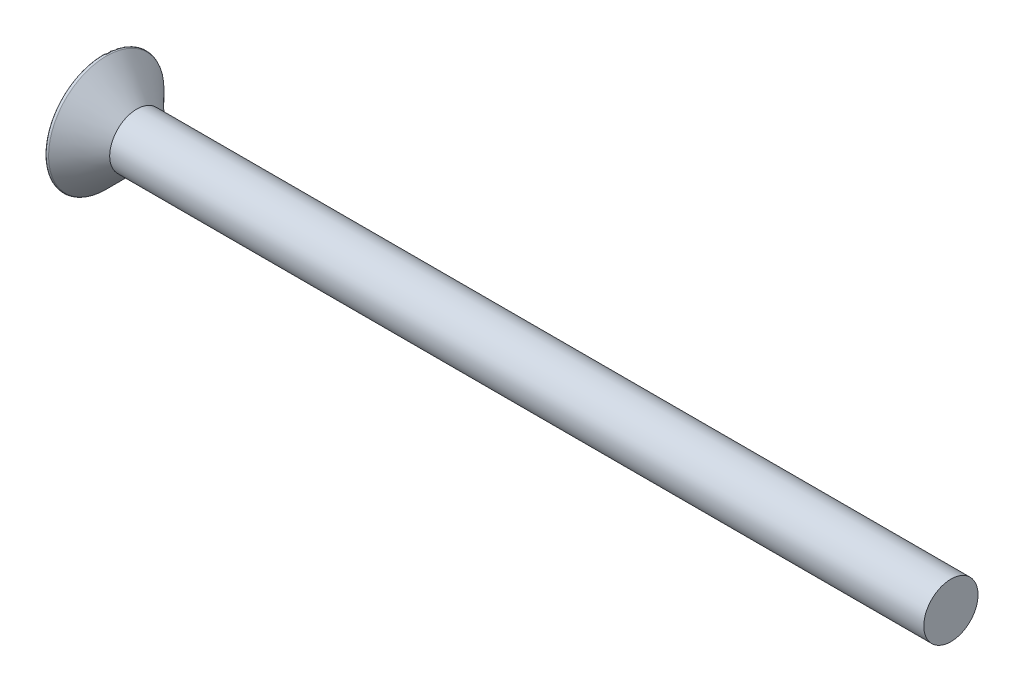
SolidWorks part; units mm, degrees
ref_plane "Plan de face" through (0, 0, 0) normal (0, 0, 1) x (1, 0, 0)
ref_plane "Plan de dessus" through (0, 0, 0) normal (0, 1, 0) x (1, 0, 0)
ref_plane "Plan de droite" through (0, 0, 0) normal (1, 0, 0) x (0, 0, -1)
sketch "Esquisse1" plane through (0, 0, 0) normal (0, 0, 1) x (1, 0, 0)
  line L0 (0, 0) -> (46.86, 0) construction
  line L1 (0, 0) -> (0, 3.36)
  line L2 (0, 3.36) -> (1.86, 1.5)
  line L3 (1.86, 1.5) -> (46.86, 1.5)
  line L4 (46.86, 1.5) -> (46.86, 0)
  line L5 (0, 0) -> (46.86, 0)
  dimension "D1" = 3.36
  dimension "D2" = 1.86
  dimension "D3" = 45
  dimension "D4" = 45
revolve "Révolution1" add sketch "Esquisse1" angle 360 about L0
fillet "Congé1" radius 0.1 1 edges at (0, 0, 3.36)
